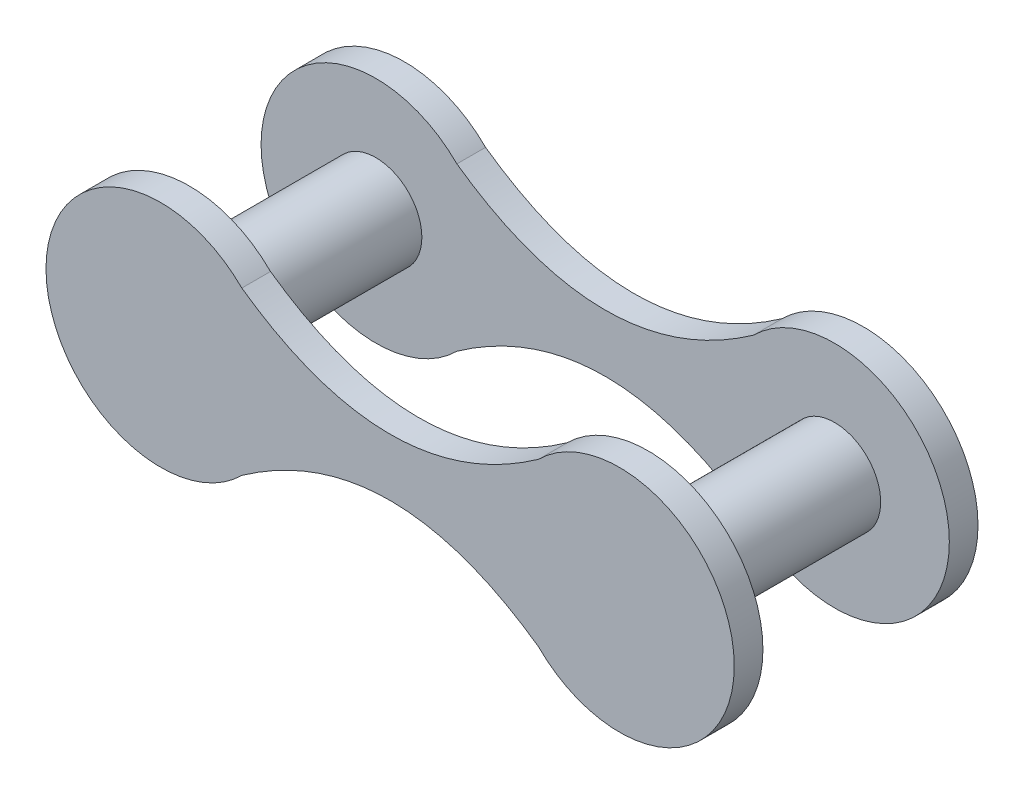
SolidWorks part; units mm, degrees
ref_plane "Front Plane" through (0, 0, 0) normal (0, 0, 1) x (1, 0, 0)
ref_plane "Top Plane" through (0, 0, 0) normal (0, 1, 0) x (1, 0, 0)
ref_plane "Right Plane" through (0, 0, 0) normal (1, 0, 0) x (0, 0, -1)
sketch "Sketch1" plane through (0, 0, 0) normal (0, 0, 1) x (1, 0, 0)
  line L0 (-6.35, 0) -> (6.35, 0) construction
  line L1 (-6.35, 0) -> (-6.35, 5.3941) construction
  line L2 (0, -9.5021) -> (0, 10.9777) construction
  line L3 (-6.35, 0) -> (0, 6.35) construction
  line L4 (0, 6.35) -> (6.35, 0) construction
  line L5 (-2.1004, 0.7937) -> (1.9982, 0.7937) construction
  arc A0 (-4.1049, 2.2451) -> (-4.1049, -2.2451) centre (-6.35, 0) ccw
  arc A1 (4.1049, -2.2451) -> (4.1049, 2.2451) centre (6.35, 0) ccw
  spline S0 degree 2 poles (-4.1049, 2.2451) (0, -0.6576) (4.1049, 2.2451) knots 0 0 0 1 1 1
  spline S1 degree 2 poles (-4.1049, -2.2451) (0, 0.6576) (4.1049, -2.2451) knots 0 0 0 1 1 1
  point P7 (-4.1049, 2.2451)
  point P12 (4.1049, 2.2451)
  dimension "D1" = 6.35
  dimension "D2" = 6.35
  dimension "D3" = 12.7
  dimension "D4" = 0.7937
extrude "Boss-Extrude1" add sketch "Sketch1" along normal blind 0.7937
sketch "Sketch2" plane through (0, 0, 0.7937) normal (0, 0, 1) x (1, 0, 0)
  line L0 (0, 3.0728) -> (0, -3.9301) construction
  line L1 (0, -9.5021) -> (0, 10.9777) construction
  circle A0 centre (-6.35, 0) radius 1.2753
  circle A1 centre (6.35, 0) radius 1.2753
  point P2 (6.35, 0)
extrude "Boss-Extrude2" add sketch "Sketch2" along normal blind 5.1594
ref_plane "chianplane" through (0, 0, 3.3734) normal (0, 0, 1) x (1, 0, 0)
mirror "Mirror1" about plane through (0, 0, 3.3734) normal (0, 0, 1) of "Boss-Extrude1"
equation "\"large_diameter\" = 1/4in"
equation "\"small_diameter\" = 1/8in"
equation "\"arc_height\" = 1/32in"
equation "\"chain_space\" = 1/2in"
equation "\"chain_thickness\" = 1/32in"
equation "\"outer_height\" = 3/16in"
equation "\"inner_height\" = 2/16in"
equation "\"D1@Sketch1\" = \"large_diameter\""
equation "\"D2@Sketch1\" = \"large_diameter\""
equation "\"D3@Sketch1\"= \"chain_space\""
equation "\"D4@Sketch1\"= \"arc_height\""
equation "\"D1@Boss-Extrude1\"=\"chain_thickness\"\""
equation "\"D1@Boss-Extrude2\" = \"inner_height\" + 2 * \"chain_thickness\" + \"give\""
equation "\"give\" = 1/64in"
equation "\"D1@chianplane\"= ( \"inner_height\" + 2 * \"chain_thickness\" + \"give\" ) / 2"
